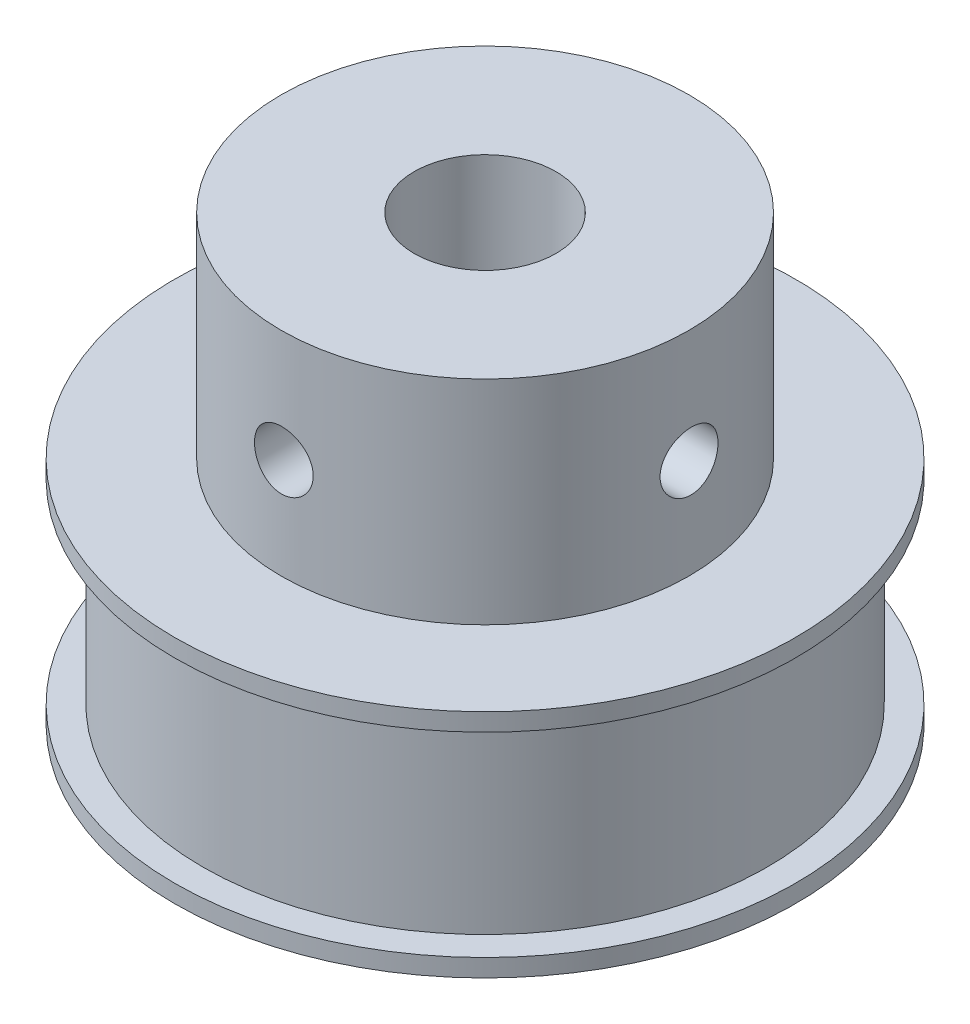
SolidWorks part; units mm, degrees
ref_plane "前视基准面" through (0, 0, 0) normal (0, 0, 1) x (1, 0, 0)
ref_plane "上视基准面" through (0, 0, 0) normal (0, 1, 0) x (1, 0, 0)
ref_plane "右视基准面" through (0, 0, 0) normal (1, 0, 0) x (0, 0, -1)
sketch "草图1" plane through (0, 0, 0) normal (0, 1, 0) x (1, 0, 0)
  circle A0 centre (0, 0) radius 17.5
  dimension "D1" = 35
extrude "凸台-拉伸1" add sketch "草图1" along normal blind 1
sketch "草图2" plane through (0, 1, 0) normal (0, 1, 0) x (1, 0, 0)
  circle A0 centre (0, 0) radius 15.915
  dimension "D1" = 31.83
extrude "凸台-拉伸2" add sketch "草图2" along normal blind 11
sketch "草图3" plane through (0, 12, 0) normal (0, 1, 0) x (1, 0, 0)
  circle A0 centre (0, 0) radius 17.5
  dimension "D1" = 35
extrude "凸台-拉伸3" add sketch "草图3" along normal blind 1
sketch "草图4" plane through (0, 13, 0) normal (0, 1, 0) x (1, 0, 0)
  circle A0 centre (0, 0) radius 11.5
  dimension "D1" = 23
extrude "凸台-拉伸4" add sketch "草图4" along normal blind 12
sketch "草图5" plane through (0, 25, 0) normal (0, 1, 0) x (1, 0, 0)
  circle A0 centre (0, 0) radius 4
  dimension "D1" = 8
extrude "切除-拉伸1" cut sketch "草图5" against normal through all contours A0
hole_wizard "M4 螺纹孔1" positions "3D草图1" profile "草图6" tap size "M4" standard "GB"
sketch3d "3D草图1"
  point P0 (11.4994, 18.5556, -0.1192)
  point P2 (0.0368, 18.6715, 11.4999)
sketch "草图6" plane through (11.4994, 18.5556, -0.1192) normal (0, 1, 0) x (-0.0104, 0, -0.9999)
  line L0 (0, 0) -> (0, 7.5)
  line L1 (0, 7.5) -> (1.65, 7.5)
  line L2 (1.65, 7.5) -> (1.65, 0)
  line L5 (1.65, 0) -> (0, 0)
  line L11 (0, -6.35) -> (0, 107.95) construction
  dimension "通孔螺纹孔钻头直径" = 3.3
  dimension "通孔螺纹孔钻头深度" = 7.5
cosmetic thread "孔螺蚊线1" parameters "D2"=4
cosmetic thread "孔螺蚊线2" parameters "D2"=4
